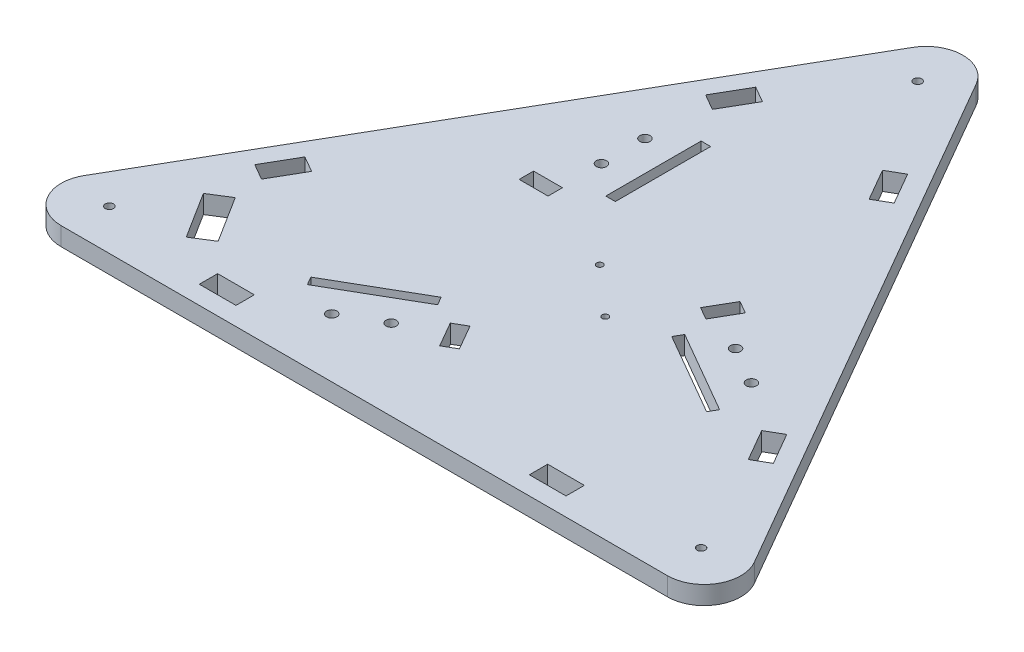
SolidWorks part; units mm, degrees
ref_plane "Front Plane" through (0, 0, 0) normal (0, 0, 1) x (1, 0, 0)
ref_plane "Top Plane" through (0, 0, 0) normal (0, 1, 0) x (1, 0, 0)
ref_plane "Right Plane" through (0, 0, 0) normal (1, 0, 0) x (0, 0, -1)
sketch "Sketch1" plane through (0, 0, 0) normal (0, 1, 0) x (1, 0, 0)
  line L1 (0, 146.647) -> (-127, -73.3235)
  line L2 (-127, -73.3235) -> (127, -73.3235)
  line L3 (127, -73.3235) -> (0, 146.647)
  circle A0 centre (0, 0) radius 73.3235 construction
  dimension "D1" = 254
extrude "Boss-Extrude1" add sketch "Sketch1" along normal blind 6.35
sketch "Sketch2" plane through (0, 6.35, 0) normal (0, 1, 0) x (1, 0, 0)
  line L0 (0, 29.8527) -> (0, 146.647)
  line L1 (51.7064, 29.8527) -> (-51.7064, 29.8527)
  line L2 (-51.7064, 29.8527) -> (0, -59.7054)
  line L3 (0, -59.7054) -> (51.7064, 29.8527)
  line L4 (-25.8532, -14.9264) -> (-127, -73.3235)
  line L5 (25.8532, -14.9264) -> (127, -73.3235)
  line L6 (0, 146.647) -> (-127, -73.3235) construction
  line L7 (-63.802, 10.7387) -> (-56.8738, 6.7387)
  line L8 (-63.802, 10.7387) -> (-73.302, -5.7158)
  line L9 (-73.302, -5.7158) -> (-66.3738, -9.7158)
  line L10 (-56.8738, 6.7387) -> (-66.3738, -9.7158)
  circle A0 centre (0, 0) radius 29.8527 construction
  line B0 (-44.7064, 46.3627) -> (-51.7064, 46.3627) construction
  line B1 (-37.558, 39.2143) -> (-37.558, 32.2143) construction
  line B2 (-37.558, 53.5111) -> (-37.558, 60.5111) construction
  line B3 (-37.558, 46.3627) -> (-42.6127, 41.308) construction
  line B4 (-42.6127, 41.308) -> (-47.5624, 36.3583) construction
  line B5 (-37.558, 46.3627) -> (-32.5033, 41.308) construction
  line B6 (-32.5033, 41.308) -> (-27.5536, 36.3583) construction
  line B7 (-37.558, 46.3627) -> (-42.6127, 51.4174) construction
  line B8 (-42.6127, 51.4174) -> (-47.5624, 56.3671) construction
  line B9 (-37.558, 46.3627) -> (-32.5033, 51.4174) construction
  line B10 (-32.5033, 51.4174) -> (-27.5536, 56.3671) construction
  line B11 (-30.4096, 46.3627) -> (-23.4096, 46.3627) construction
  line B12 (-19.558, 29.8527) -> (-19.558, 62.8727)
  line B13 (-29.558, 29.8527) -> (-29.558, 62.8727)
  line B14 (-29.558, 29.8527) -> (-19.558, 29.8527)
  line B15 (-19.558, 29.8527) -> (-19.558, 62.8727)
  line B16 (-29.558, 62.8727) -> (-19.558, 62.8727)
  line B17 (-19.558, 29.8527) -> (-16.256, 29.8527)
  line B18 (-19.558, 62.8727) -> (-16.256, 62.8727)
  line B19 (-16.256, 29.8527) -> (-16.256, 62.8727)
  line B20 (-16.256, 29.8527) -> (-16.256, 62.8727)
  line B21 (-16.256, 29.8527) -> (0, 29.8527)
  line B22 (-16.256, 62.8727) -> (0, 62.8727)
  line B23 (0, 29.8527) -> (0, 62.8727)
  line B24 (-23.4096, 46.3627) -> (-19.558, 46.3627) construction
  circle B25 centre (-37.558, 46.3627) radius 7.1484
  circle B26 centre (-37.558, 46.3627) radius 14.1484
  circle B27 centre (-37.558, 35.7143) radius 1.397
  circle B28 centre (-30.0284, 38.8331) radius 1.778
  circle B29 centre (-30.0284, 53.8923) radius 1.778
  circle B30 centre (-37.558, 57.0111) radius 1.397
  circle B31 centre (-45.0876, 53.8923) radius 1.778
  circle B32 centre (-48.2064, 46.3627) radius 1.397
  circle B33 centre (-45.0876, 38.8331) radius 1.778
  circle B34 centre (-26.9096, 46.3627) radius 1.397
  line B35 (-17.7981, -61.8982) -> (-14.2981, -67.9604) construction
  line B36 (-15.1816, -52.1333) -> (-9.1194, -48.6333) construction
  line B37 (-27.563, -59.2817) -> (-33.6251, -62.7817) construction
  line B38 (-21.3723, -55.7075) -> (-14.4675, -57.5577) construction
  line B39 (-14.4675, -57.5577) -> (-7.706, -59.3694) construction
  line B40 (-21.3723, -55.7075) -> (-19.5221, -48.8027) construction
  line B41 (-19.5221, -48.8027) -> (-17.7104, -42.0412) construction
  line B42 (-21.3723, -55.7075) -> (-23.2224, -62.6124) construction
  line B43 (-23.2224, -62.6124) -> (-25.0342, -69.3738) construction
  line B44 (-21.3723, -55.7075) -> (-28.2771, -53.8574) construction
  line B45 (-28.2771, -53.8574) -> (-35.0386, -52.0457) construction
  line B46 (-24.9465, -49.5168) -> (-28.4465, -43.4547) construction
  line B47 (-16.0742, -31.8641) -> (-44.6704, -48.3741)
  line B48 (-11.0742, -40.5243) -> (-39.6704, -57.0343)
  line B49 (-11.0742, -40.5243) -> (-16.0742, -31.8641)
  line B50 (-16.0742, -31.8641) -> (-44.6704, -48.3741)
  line B51 (-39.6704, -57.0343) -> (-44.6704, -48.3741)
  line B52 (-16.0742, -31.8641) -> (-17.7252, -29.0045)
  line B53 (-44.6704, -48.3741) -> (-46.3214, -45.5145)
  line B54 (-17.7252, -29.0045) -> (-46.3214, -45.5145)
  line B55 (-17.7252, -29.0045) -> (-46.3214, -45.5145)
  line B56 (-17.7252, -29.0045) -> (-25.8532, -14.9264)
  line B57 (-46.3214, -45.5145) -> (-54.4494, -31.4364)
  line B58 (-25.8532, -14.9264) -> (-54.4494, -31.4364)
  line B59 (-28.4465, -43.4547) -> (-30.3723, -40.1191) construction
  circle B60 centre (-21.3723, -55.7075) radius 7.1484
  circle B61 centre (-21.3723, -55.7075) radius 14.1484
  circle B62 centre (-12.1505, -50.3833) radius 1.397
  circle B63 centre (-18.6163, -45.422) radius 1.778
  circle B64 centre (-31.6578, -52.9515) radius 1.778
  circle B65 centre (-30.5941, -61.0317) radius 1.397
  circle B66 centre (-24.1283, -65.9931) radius 1.778
  circle B67 centre (-16.0481, -64.9293) radius 1.397
  circle B68 centre (-11.0867, -58.4635) radius 1.778
  circle B69 centre (-26.6965, -46.4858) radius 1.397
  line B70 (62.5045, 15.5355) -> (66.0045, 21.5977) construction
  line B71 (52.7396, 12.919) -> (46.6774, 16.419) construction
  line B72 (65.121, 5.7706) -> (71.1831, 2.2706) construction
  line B73 (58.9303, 9.3448) -> (57.0801, 16.2497) construction
  line B74 (57.0801, 16.2497) -> (55.2684, 23.0111) construction
  line B75 (58.9303, 9.3448) -> (52.0255, 7.4947) construction
  line B76 (52.0255, 7.4947) -> (45.264, 5.683) construction
  line B77 (58.9303, 9.3448) -> (65.8351, 11.195) construction
  line B78 (65.8351, 11.195) -> (72.5966, 13.0067) construction
  line B79 (58.9303, 9.3448) -> (60.7804, 2.44) construction
  line B80 (60.7804, 2.44) -> (62.5922, -4.3215) construction
  line B81 (55.3561, 3.1541) -> (51.8561, -2.908) construction
  line B82 (35.6322, 2.0114) -> (64.2284, -14.4986)
  line B83 (40.6322, 10.6716) -> (69.2284, -5.8384)
  line B84 (40.6322, 10.6716) -> (35.6322, 2.0114)
  line B85 (35.6322, 2.0114) -> (64.2284, -14.4986)
  line B86 (69.2284, -5.8384) -> (64.2284, -14.4986)
  line B87 (35.6322, 2.0114) -> (33.9812, -0.8482)
  line B88 (64.2284, -14.4986) -> (62.5774, -17.3582)
  line B89 (33.9812, -0.8482) -> (62.5774, -17.3582)
  line B90 (33.9812, -0.8482) -> (62.5774, -17.3582)
  line B91 (33.9812, -0.8482) -> (25.8532, -14.9264)
  line B92 (62.5774, -17.3582) -> (54.4494, -31.4364)
  line B93 (25.8532, -14.9264) -> (54.4494, -31.4364)
  line B94 (51.8561, -2.908) -> (49.9303, -6.2436) construction
  circle B95 centre (58.9303, 9.3448) radius 7.1484
  circle B96 centre (58.9303, 9.3448) radius 14.1484
  circle B97 centre (49.7085, 14.669) radius 1.397
  circle B98 centre (48.6447, 6.5888) radius 1.778
  circle B99 centre (61.6863, -0.9407) radius 1.778
  circle B100 centre (68.1521, 4.0206) radius 1.397
  circle B101 centre (69.2158, 12.1008) radius 1.778
  circle B102 centre (64.2545, 18.5666) radius 1.397
  circle B103 centre (56.1743, 19.6304) radius 1.778
  circle B104 centre (53.6061, 0.1231) radius 1.397
  dimension "D1" = 19
  dimension "D2" = 8
  dimension "D3" = 12.7
sketch_block_instance "Servo_Brackets_BlockV2-1"
sketch_block "Servo_Brackets_BlockV2" parameters "D2"=2.794, "D3"=3.556, "D1"=7, "D4"=10, "D5"=33.02, "D6"=3.302, "D7"=16.256, "D8"=18
sketch_block_instance "Servo_Brackets_BlockV2-2"
sketch_block_instance "Servo_Brackets_BlockV2-3"
extrude "Cut-Extrude1" cut sketch "Sketch2" against normal through all contours L1 B19 B18 B12 | L2 B54 B53 B47 | B13 B28 | B13 B28 | B13 B29 | B13 B29 | B48 B64 | B48 B64 | B48 B63 | B48 B63 | L3 B89 B88 B82 | B83 B98 | B83 B99 | B83 B99 | B83 B98 | B32 | B68 | B31 | B33
sketch "Sketch3" plane through (0, 6.35, 0) normal (0, 1, 0) x (1, 0, 0)
  line L0 (63.5, 36.6617) -> (51.4016, 29.6767)
  line L1 (22.225, 108.1521) -> (104.775, -34.8287)
  line L2 (22.225, 108.1521) -> (10.1266, 101.1671)
  line L3 (10.1266, 101.1671) -> (92.6766, -41.8137)
  line L4 (104.775, -34.8287) -> (92.6766, -41.8137)
  line L5 (-63.5, 36.6617) -> (-51.4016, 29.6767)
  line L6 (-104.775, -34.8287) -> (-22.225, 108.1521)
  line L7 (-104.775, -34.8287) -> (-92.6766, -41.8137)
  line L8 (-92.6766, -41.8137) -> (-10.1266, 101.1671)
  line L9 (-22.225, 108.1521) -> (-10.1266, 101.1671)
  line L10 (0, -59.3535) -> (0, -73.3235)
  line L11 (-82.55, -59.3535) -> (82.55, -59.3535)
  line L12 (-82.55, -59.3535) -> (-82.55, -73.3235)
  line L13 (-82.55, -73.3235) -> (82.55, -73.3235)
  line L14 (82.55, -59.3535) -> (82.55, -73.3235)
  line L15 (127, -73.3235) -> (0, 146.647) construction
  line L16 (0, 146.647) -> (-127, -73.3235) construction
  line L17 (-127, -73.3235) -> (127, -73.3235) construction
  line L18 (-22.225, 108.1521) -> (22.225, 108.1521)
  line L19 (-104.775, -34.8287) -> (-82.55, -73.3235)
  line L20 (104.775, -34.8287) -> (82.55, -73.3235)
  line L21 (35.3209, 21.4723) -> (30.3209, 12.812)
  line L22 (-29.558, 24.8527) -> (-39.558, 24.8527)
  line L23 (-29.558, 24.8527) -> (-29.558, 19.8527)
  line L24 (-29.558, 19.8527) -> (-39.558, 19.8527)
  line L25 (-39.558, 24.8527) -> (-39.558, 19.8527)
  line L26 (35.3209, 21.4723) -> (39.6511, 18.9723)
  line L27 (39.6511, 18.9723) -> (34.6511, 10.312)
  line L28 (30.3209, 12.812) -> (34.6511, 10.312)
  line L29 (0.9351, -41.325) -> (-4.0649, -32.6647)
  line L30 (0.9351, -41.325) -> (-3.3951, -43.825)
  line L31 (-3.3951, -43.825) -> (-8.3951, -35.1647)
  line L32 (-4.0649, -32.6647) -> (-8.3951, -35.1647)
  line L33 (-16.256, 29.8527) -> (-19.558, 29.8527) construction
  line L34 (33.9812, -0.8482) -> (35.6322, 2.0114) construction
  line L35 (-17.7252, -29.0045) -> (-16.0742, -31.8641) construction
  line L36 (-19.558, 29.8527) -> (-19.558, 62.8727) construction
  line L37 (33.9812, -0.8482) -> (62.5774, -17.3582) construction
  line L38 (-17.7252, -29.0045) -> (-46.3214, -45.5145) construction
  circle A0 centre (102.4613, -59.1561) radius 1.4224
  circle A1 centre (0, 118.3121) radius 1.4224
  circle A2 centre (-102.4613, -59.1561) radius 1.4224
  point P51 (-17.907, 29.8527)
  dimension "D7" = 2.8448
  dimension "D20" = 10.16
  dimension "D1" = 165.1
  dimension "D2" = 10.16
  dimension "D3" = 165.1
  dimension "D4" = 13.97
  dimension "D5" = 165.1
  dimension "D6" = 13.97
  dimension "D8" = 10
  dimension "D9" = 5
  dimension "D10" = 10
  dimension "D11" = 5
  dimension "D12" = 10
  dimension "D13" = 5
  dimension "D14" = 10
  dimension "D15" = 5
  dimension "D16" = 10
  dimension "D17" = 5
  dimension "D18" = 10
  dimension "D19" = 5
  dimension "D21" = 10.16
extrude "Cut-Extrude2" cut sketch "Sketch3" against normal through all contours A1 | A2 | A0 | L22 L25 L24 L23 | L29 L32 L31 L30 | L21 L28 L27 L26
sketch "Sketch4" plane through (0, 6.35, 0) normal (0, 1, 0) x (1, 0, 0)
  line L1 (16.51, -6.3973) -> (16.51, 8.2077) construction
  line L2 (16.51, -6.3973) -> (0, -6.3973) construction
  line L3 (0, -6.3973) -> (0, 8.2077) construction
  line L4 (16.51, 8.2077) -> (0, 8.2077) construction
  circle A0 centre (0, 8.2077) radius 1.0922
  circle A1 centre (16.51, -6.3973) radius 1.0922
  dimension "D3" = 2.1844
  dimension "D4" = 2.1844
  dimension "D1" = 14.605
  dimension "D2" = 16.51
extrude "Cut-Extrude3" cut sketch "Sketch4" against normal through all
fillet "Fillet1" radius 12.7 3 edges at (0, 3.175, -146.647) (127, 3.175, 73.3235) (-127, 3.175, 73.3235)
sketch "Sketch5" plane through (0, 6.35, 0) normal (0, 1, 0) x (1, 0, 0)
  line L0 (-10.9985, 127.597) -> (-116.0015, -54.2735) construction
  line L1 (116.0015, -54.2735) -> (10.9985, 127.597) construction
  line L2 (-105.003, -73.3235) -> (105.003, -73.3235) construction
  line B0 (57.8823, 33.6919) -> (52.383, 30.5169)
  line B1 (96.833, -46.4728) -> (102.3323, -43.2978)
  line B2 (96.833, -46.4728) -> (7.933, 107.5066)
  line B3 (7.933, 107.5066) -> (13.4323, 110.6816)
  line B4 (102.3323, -43.2978) -> (13.4323, 110.6816)
  line B5 (89.6323, -21.3007) -> (84.133, -24.4757)
  line B6 (89.6323, -21.3007) -> (83.2823, -10.3022)
  line B7 (83.2823, -10.3022) -> (77.783, -13.4772)
  line B8 (84.133, -24.4757) -> (77.783, -13.4772)
  line B9 (32.4823, 77.686) -> (26.983, 74.511)
  line B10 (32.4823, 77.686) -> (26.1323, 88.6845)
  line B11 (26.1323, 88.6845) -> (20.633, 85.5095)
  line B12 (26.983, 74.511) -> (20.633, 85.5095)
  line B13 (102.3323, -43.2978) -> (107.8316, -40.1228)
  line B14 (102.3323, -43.2978) -> (13.4323, 110.6816)
  line B15 (13.4323, 110.6816) -> (18.9316, 113.8566)
  line B16 (107.8316, -40.1228) -> (18.9316, 113.8566)
  line B17 (0, -66.9735) -> (0, -60.6235)
  line B18 (-88.9, -60.6235) -> (-88.9, -66.9735)
  line B19 (-88.9, -60.6235) -> (88.9, -60.6235)
  line B20 (88.9, -60.6235) -> (88.9, -66.9735)
  line B21 (-88.9, -66.9735) -> (88.9, -66.9735)
  line B22 (-63.5, -66.9735) -> (-63.5, -60.6235)
  line B23 (-63.5, -66.9735) -> (-50.8, -66.9735)
  line B24 (-50.8, -66.9735) -> (-50.8, -60.6235)
  line B25 (-63.5, -60.6235) -> (-50.8, -60.6235)
  line B26 (50.8, -66.9735) -> (50.8, -60.6235)
  line B27 (50.8, -66.9735) -> (63.5, -66.9735)
  line B28 (63.5, -66.9735) -> (63.5, -60.6235)
  line B29 (50.8, -60.6235) -> (63.5, -60.6235)
  line B30 (-88.9, -66.9735) -> (-88.9, -73.3235)
  line B31 (-88.9, -66.9735) -> (88.9, -66.9735)
  line B32 (88.9, -66.9735) -> (88.9, -73.3235)
  line B33 (-88.9, -73.3235) -> (88.9, -73.3235)
  line B34 (-58.0007, 33.4867) -> (-52.5015, 30.3117)
  line B35 (-8.0515, 107.3014) -> (-13.5507, 110.4764)
  line B36 (-8.0515, 107.3014) -> (-96.9515, -46.6779)
  line B37 (-96.9515, -46.6779) -> (-102.4507, -43.5029)
  line B38 (-13.5507, 110.4764) -> (-102.4507, -43.5029)
  line B39 (-26.2507, 88.4794) -> (-20.7515, 85.3044)
  line B40 (-26.2507, 88.4794) -> (-32.6007, 77.4808)
  line B41 (-32.6007, 77.4808) -> (-27.1015, 74.3058)
  line B42 (-20.7515, 85.3044) -> (-27.1015, 74.3058)
  line B43 (-83.4007, -10.5073) -> (-77.9015, -13.6823)
  line B44 (-83.4007, -10.5073) -> (-89.7507, -21.5059)
  line B45 (-89.7507, -21.5059) -> (-84.2515, -24.6809)
  line B46 (-77.9015, -13.6823) -> (-84.2515, -24.6809)
  line B47 (-13.5507, 110.4764) -> (-19.05, 113.6514)
  line B48 (-13.5507, 110.4764) -> (-102.4507, -43.5029)
  line B49 (-102.4507, -43.5029) -> (-107.95, -40.3279)
  line B50 (-19.05, 113.6514) -> (-107.95, -40.3279)
sketch_block_instance "Base_Side_Block-1"
sketch_block "Base_Side_Block" parameters "D1"=177.8, "D2"=6.35, "D3"=25.4, "D4"=25.4, "D5"=12.7, "D6"=12.7, "D7"=6.35
sketch_block_instance "Base_Side_Block-2"
sketch_block_instance "Base_Side_Block-3"
extrude "Cut-Extrude4" cut sketch "Sketch5" against normal through all contours B21 B24 B19 B22 | B21 B28 B19 B26 | B4 B7 B2 B5 | B4 B11 B2 B9 | B38 B41 B36 B39 | B38 B45 B36 B43
sketch "Sketch6" plane through (0, 6.35, 0) normal (0, 1, 0) x (1, 0, 0)
  line L1 (-73.1252, -50.8334) -> (-83.259, -34.7616)
  line L2 (-73.1252, -50.8334) -> (-79.8922, -55.1003)
  line L3 (-79.8922, -55.1003) -> (-90.0261, -39.0285)
  line L4 (-83.259, -34.7616) -> (-90.0261, -39.0285)
  dimension "D1" = 8
  dimension "D2" = 19
extrude "Cut-Extrude5" cut sketch "Sketch6" against normal through all
